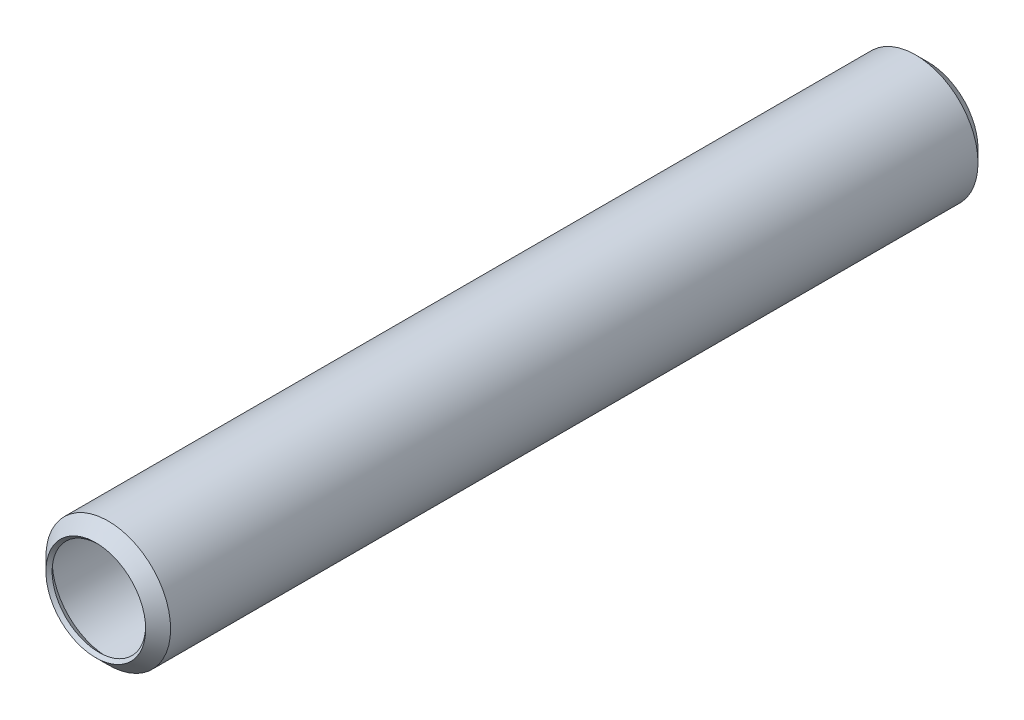
SolidWorks part; units mm, degrees
ref_plane "Alzado" through (0, 0, 0) normal (0, 0, 1) x (1, 0, 0)
ref_plane "Planta" through (0, 0, 0) normal (0, 1, 0) x (1, 0, 0)
ref_plane "Vista lateral" through (0, 0, 0) normal (1, 0, 0) x (0, 0, -1)
sketch "Croquis1" plane through (0, 0, 0) normal (0, 1, 0) x (1, 0, 0)
  circle A0 centre (0, 0) radius 10
  circle A1 centre (0, 0) radius 9
  dimension "D1" = 20
  dimension "D2" = 18
sketch "Croquis4" plane through (0, 0, 0) normal (1, 0, 0) x (0, 0, -1)
  line L0 (0, 0) -> (0, 10) construction
  line L1 (-64.75, 10) -> (64.75, 10)
  line L3 (-64.75, 9) -> (64.75, 9)
  line L4 (64.75, 9) -> (66.25, 7.5)
  line L5 (66.25, 7.5) -> (66.75, 8)
  line L6 (66.75, 8) -> (64.75, 10)
  line L7 (-66.75, 8) -> (-64.75, 10)
  line L8 (-66.25, 7.5) -> (-66.75, 8)
  line L9 (-64.75, 9) -> (-66.25, 7.5)
  line L11 (0, 0) -> (13.9507, 0) construction
  dimension "D1" = 10
  dimension "D2" = 64.75
  dimension "D3" = 135
  dimension "D4" = 135
  dimension "D5" = 1
  dimension "D6" = 2
revolve "Revolución1" add sketch "Croquis4" angle 360 about L11
